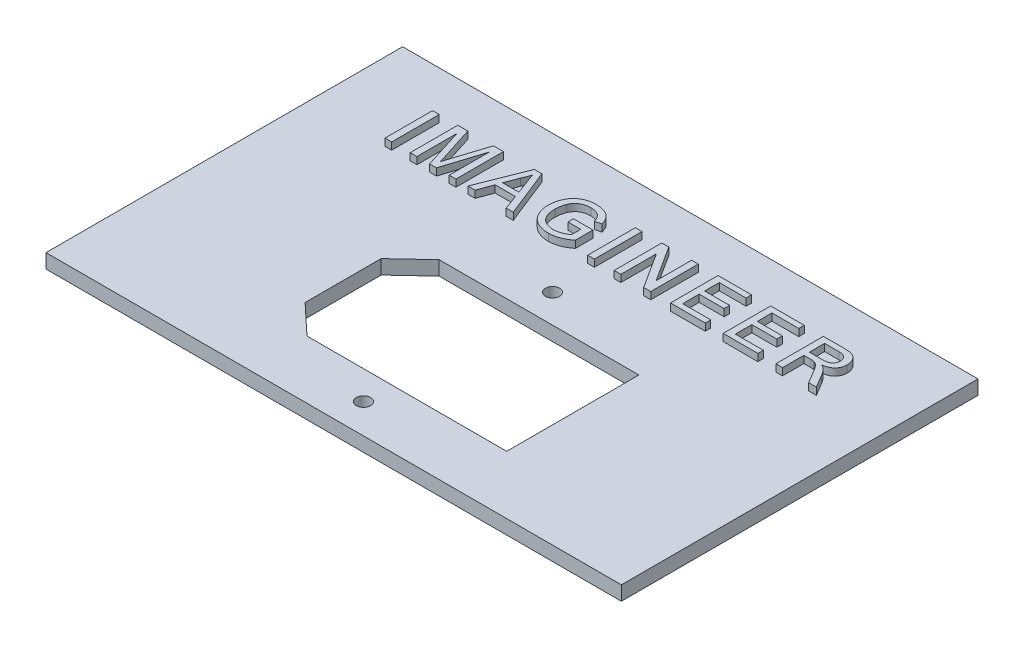
SolidWorks part; units mm, degrees
ref_plane "Front Plane" through (0, 0, 0) normal (0, 0, 1) x (1, 0, 0)
ref_plane "Top Plane" through (0, 0, 0) normal (0, 1, 0) x (1, 0, 0)
ref_plane "Right Plane" through (0, 0, 0) normal (1, 0, 0) x (0, 0, -1)
sketch "Sketch1" plane through (0, 0, 0) normal (0, 1, 0) x (1, 0, 0)
  line L1 (0, 0) -> (121, 0)
  line L2 (0, 0) -> (0, 75)
  line L3 (0, 75) -> (121, 75)
  line L4 (121, 0) -> (121, 75)
  dimension "D1" = 121
  dimension "D2" = 75
extrude "Boss-Extrude1" add sketch "Sketch1" along normal blind 58
sketch "Sketch2" plane through (0, 0, -75) normal (0, 0, -1) x (-1, 0, 0)
  line L0 (-121, 0) -> (0, 0) construction
  line L1 (-3, 3) -> (-118, 3)
  line L2 (-3, 3) -> (-3, 55)
  line L3 (-3, 55) -> (-118, 55)
  line L4 (-118, 3) -> (-118, 55)
  line L5 (0, 58) -> (0, 0) construction
  line L6 (-121, 58) -> (-121, 0) construction
  dimension "D1" = 52
  dimension "D2" = 3
  dimension "D3" = 3
  dimension "D4" = 3
extrude "Cut-Extrude1" cut sketch "Sketch2" against normal blind 72
sketch "Sketch4" plane through (0, 58, 0) normal (0, 1, 0) x (1, 0, 0)
  text T0 "IMAGINEER" height 10
  point P1 (10.2539, 54.8174)
  point P2 (13.2882, 55.256)
  point P3 (0, 0)
  point P4 (0, 0)
extrude "Boss-Extrude2" add sketch "Sketch4" along normal blind 1.5
sketch "Sketch5" plane through (0, 58, 0) normal (0, 1, 0) x (-1, 0, 0)
  line L12 (-60.5, 72.992) -> (-60.5, -137.1284) construction
  line L13 (-84.629, -12.2531) -> (-42.629, -12.2531)
  line L14 (-42.629, -12.2531) -> (-36.329, -18.1531)
  line L15 (-36.329, -18.1531) -> (-36.329, -34.1531)
  line L16 (-36.329, -34.1531) -> (-42.629, -40.0531)
  line L17 (-84.629, -12.2531) -> (-84.629, -40.0531)
  line L18 (-84.629, -40.0531) -> (-42.629, -40.0531)
  circle A4 centre (-60.4781, -46.043) radius 1.4898
  circle A5 centre (-60.5065, -6.2504) radius 1.5
  point P0 (0, 0)
  point P2 (0, 0)
  point P7 (0, 0)
  dimension "D1" = 60.5
extrude "Cut-Extrude2" cut sketch "Sketch5" against normal blind 5
sketch "Sketch6" plane through (121, 0, 0) normal (1, 0, 0) x (0, 0, -1)
  line L0 (75, 58) -> (75, 0) construction
  line L1 (0, 0) -> (75, 0)
  line L2 (0, 0) -> (0, 3)
  line L3 (0, 3) -> (75, 3)
  line L4 (75, 0) -> (75, 3)
  dimension "D1" = 3
extrude "Boss-Extrude3" add sketch "Sketch6" along normal blind 20
sketch "Sketch7" plane through (0, 3, 0) normal (0, 1, 0) x (1, 0, 0)
  line L0 (141, 75) -> (141, 0) construction
  line L1 (141, 75) -> (121, 75) construction
  line L2 (141, 0) -> (121, 0) construction
  circle A0 centre (131, 63) radius 2.5
  circle A1 centre (131, 37.5) radius 2.5
  circle A2 centre (131, 12) radius 2.5
  point P12 (0, 0)
  dimension "D1" = 5
  dimension "D2" = 10
  dimension "D3" = 12
  dimension "D4" = 12
  dimension "D5" = 25.5
extrude "Cut-Extrude3" cut sketch "Sketch7" against normal blind 20
sketch "Sketch8" plane through (0, 0, 0) normal (0, 0, 1) x (1, 0, 0)
  line L0 (0, 0) -> (141, 0) construction
  circle A1 centre (77.9556, 29) radius 7.5
  dimension "D1" = 29
extrude "Cut-Extrude4" cut sketch "Sketch8" against normal blind 5
sketch "Sketch9" plane through (0, 0, 0) normal (0, -1, 0) x (1, 0, 0)
  line L0 (141, -75) -> (0, -75) construction
  line L1 (0, -75) -> (0, 0) construction
  line L2 (141, 0) -> (141, -75) construction
  circle A0 centre (11, -60) radius 1.75
  circle A1 centre (110, -60) radius 1.75
  point P6 (0, 0)
  dimension "D1" = 3.5
  dimension "D2" = 15
  dimension "D3" = 11
  dimension "D4" = 31
extrude "Cut-Extrude5" cut sketch "Sketch9" against normal blind 5
sketch "Sketch11" plane through (0, 0, 0) normal (0, 0, 1) x (1, 0, 0)
  line L1 (0, 0) -> (152.7381, 0)
  line L2 (0, 0) -> (0, 55)
  line L3 (0, 55) -> (152.7381, 55)
  line L4 (152.7381, 0) -> (152.7381, 55)
  point P5 (0, 0)
  dimension "D1" = 55
extrude "Cut-Extrude7" cut sketch "Sketch11" against normal through all
